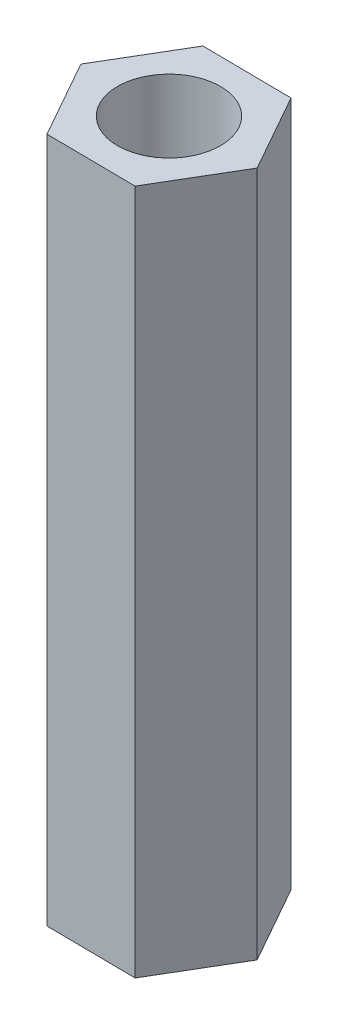
SolidWorks part; units mm, degrees
ref_plane "Front Plane" through (0, 0, 0) normal (0, 0, 1) x (1, 0, 0)
ref_plane "Top Plane" through (0, 0, 0) normal (0, 1, 0) x (1, 0, 0)
ref_plane "Right Plane" through (0, 0, 0) normal (1, 0, 0) x (0, 0, -1)
sketch "Sketch3" plane through (0, 0, 0) normal (0, 1, 0) x (1, 0, 0)
  line L1 (1.2751, -2.2636) -> (2.5979, -0.0275)
  line L2 (2.5979, -0.0275) -> (1.3228, 2.2361)
  line L3 (1.3228, 2.2361) -> (-1.2751, 2.2636)
  line L4 (-1.2751, 2.2636) -> (-2.5979, 0.0275)
  line L5 (-2.5979, 0.0275) -> (-1.3228, -2.2361)
  line L6 (-1.3228, -2.2361) -> (1.2751, -2.2636)
  circle A0 centre (0, 0) radius 2.25 construction
  dimension "D1" = 4.5
extrude "Boss-Extrude2" add sketch "Sketch3" along normal blind 20
sketch "Sketch4" plane through (0, 20, 0) normal (0, 1, 0) x (1, 0, 0)
  circle A0 centre (0, 0) radius 1.5
  dimension "D1" = 3
extrude "Cut-Extrude2" cut sketch "Sketch4" against normal up to surface (20 mm away) up to face at (0, 0, 0)
